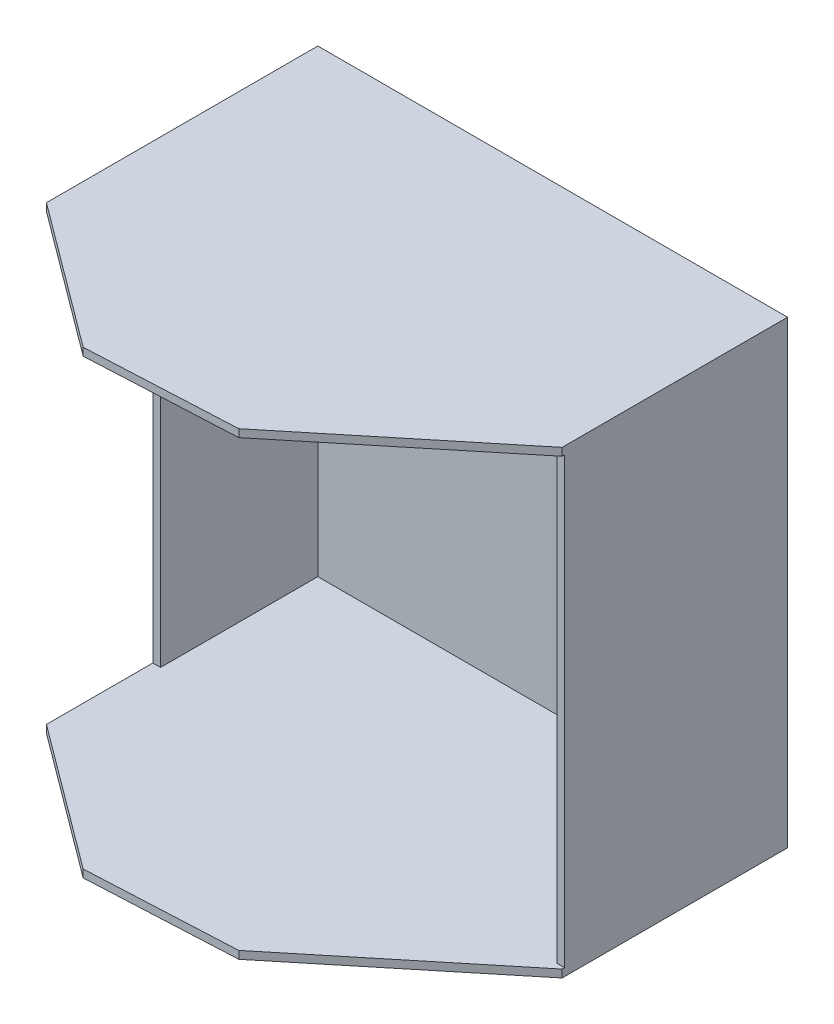
SolidWorks part; units mm, degrees
ref_plane "Front Plane" through (0, 0, 0) normal (0, 0, 1) x (1, 0, 0)
ref_plane "Top Plane" through (0, 0, 0) normal (0, 1, 0) x (1, 0, 0)
ref_plane "Right Plane" through (0, 0, 0) normal (1, 0, 0) x (0, 0, -1)
sketch "Sketch1" plane through (0, 0, 0) normal (0, 1, 0) x (1, 0, 0)
  line L0 (-71.1993, 0) -> (119.8007, 0)
  line L1 (119.8007, 0) -> (119.8007, -90)
  line L2 (119.8007, -90) -> (46.2729, -150.1553)
  line L3 (46.2729, -150.1553) -> (-15.0357, -153.1811)
  line L4 (-15.0357, -153.1811) -> (-74.3993, -109)
  line L5 (-74.3993, -109) -> (-74.3993, -65)
  line L6 (-74.3993, -65) -> (-71.1993, -65)
  line L7 (-71.1993, -65) -> (-71.1993, 0)
  point P6 (46.9827, -141.4423)
  point P10 (-15.9614, -145.1449)
  point P11 (40.0403, -150.2359)
  point P12 (-15.0357, -153.2422)
  dimension "D1" = 191
  dimension "D2" = 90
  dimension "D3" = 74
  dimension "D4" = 95
  dimension "D6" = 65
  dimension "D7" = 3.2
  dimension "D9" = 44
extrude "Boss-Extrude1" add sketch "Sketch1" along normal blind 3.2
sketch "Sketch3" plane through (0, 0, 0) normal (0, -1, 0) x (1, 0, 0)
  line L1 (-74.3993, 108.0683) -> (119.7657, 108.4369) construction
  line L2 (-74.3993, 65) -> (-74.3993, 109) construction
  line L3 (-5.3993, 152.7055) -> (-5.3993, 0) construction
  line L4 (-15.0357, 153.1811) -> (46.2729, 150.1553) construction
  line L5 (119.8007, 0) -> (-71.1993, 0) construction
  circle A0 centre (-5.3993, 108.1993) radius 12.3
  dimension "D3" = 24.6
  dimension "D1" = 45
  dimension "D2" = 69
extrude "Boss-Extrude2" add sketch "Sketch3" along normal blind 3.2
sketch "Sketch4" plane through (0, -3.2, 0) normal (0, -1, 0) x (1, 0, 0)
  circle A0 centre (-5.3993, 108.1993) radius 4
  dimension "D1" = 8
extrude "Boss-Extrude3" add sketch "Sketch4" along normal blind 4
sketch "Sketch6" plane through (0, 0, 0) normal (0, 1, 0) x (1, 0, 0)
  line L0 (-74.3993, -65) -> (-74.3993, 0)
  line L1 (-74.3993, 0) -> (-71.1993, 0)
  line L2 (-71.1993, 0) -> (-71.1993, -65)
  line L3 (-71.1993, -65) -> (-74.3993, -65)
extrude "Boss-Extrude4" add sketch "Sketch6" along normal blind 190
sketch "Sketch8" plane through (0, 0, 0) normal (0, 1, 0) x (1, 0, 0)
  line L0 (119.8007, 0) -> (116.6007, 0)
  line L1 (119.8007, 0) -> (-71.1993, 0) construction
  line L2 (116.6007, 0) -> (116.6007, -89)
  line L3 (116.6007, -89) -> (119.8007, -89)
  line L4 (119.8007, -90) -> (119.8007, 0) construction
  line L5 (119.8007, -89) -> (119.8007, 0)
  dimension "D1" = 3.2
  dimension "D2" = 89
extrude "Boss-Extrude5" add sketch "Sketch8" along normal blind 190
ref_plane "Plane2" through (0, 95, 0) normal (0, -1, 0) x (-1, 0, 0)
mirror "Mirror1" about plane through (0, 95, 0) normal (0, -1, 0) of "Boss-Extrude1"
sketch "Sketch9" plane through (0, 0, 0) normal (0, 0, 1) x (1, 0, 0)
  line L0 (22.7007, 190) -> (22.7007, 0) construction
  line L3 (-74.3993, 95) -> (119.8007, 95) construction
  line L4 (-74.3993, 186.8) -> (-74.3993, 3.2) construction
  line L5 (119.8007, 186.8) -> (119.8007, 3.2) construction
  line L6 (119.8007, 190) -> (-74.3993, 190) construction
  line L7 (119.8007, 0) -> (-74.3993, 0) construction
  line L8 (119.8007, 190) -> (119.8007, 0) construction
  line L9 (-74.3993, 0) -> (119.8007, 0)
  line L10 (-74.3993, 0) -> (-74.3993, 190)
  line L11 (-74.3993, 190) -> (119.8007, 190)
  line L12 (119.8007, 0) -> (119.8007, 190)
  line L13 (-74.3993, 0) -> (119.8007, 190) construction
  line L14 (-74.3993, 190) -> (119.8007, 0) construction
  point P12 (22.7007, 95)
extrude "Boss-Extrude7" add sketch "Sketch9" against normal blind 3.2
